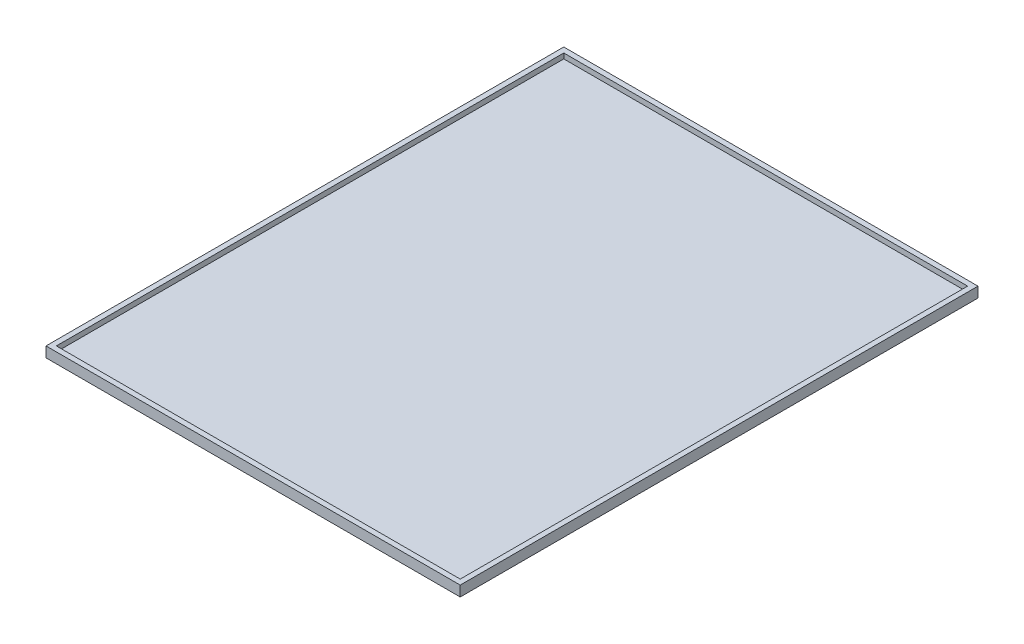
SolidWorks part; units mm, degrees
ref_plane "Front" through (0, 0, 0) normal (0, 0, 1) x (1, 0, 0)
ref_plane "Top" through (0, 0, 0) normal (0, 1, 0) x (1, 0, 0)
ref_plane "Right" through (0, 0, 0) normal (1, 0, 0) x (0, 0, -1)
sketch "Sketch1" plane through (0, 0, 0) normal (0, 1, 0) x (1, 0, 0)
  line L1 (0, 0) -> (400, 0)
  line L2 (0, 0) -> (0, 500)
  line L3 (0, 500) -> (400, 500)
  line L4 (400, 0) -> (400, 500)
  dimension "D1" = 400
  dimension "D2" = 500
extrude "Extrude1" add sketch "Sketch1" against normal blind 10
shell "Shell1" thickness 5
